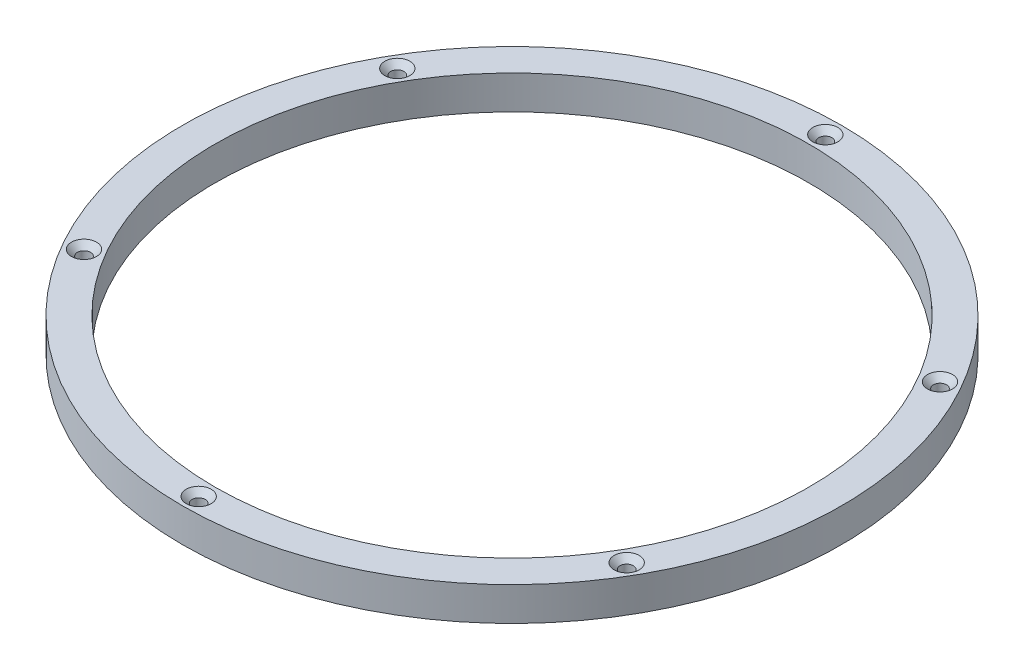
SolidWorks part; units mm, degrees
ref_plane "Front Plane" through (0, 0, 0) normal (0, 0, 1) x (1, 0, 0)
ref_plane "Top Plane" through (0, 0, 0) normal (0, 1, 0) x (1, 0, 0)
ref_plane "Right Plane" through (0, 0, 0) normal (1, 0, 0) x (0, 0, -1)
sketch "Sketch1" plane through (0, 0, 0) normal (0, 1, 0) x (1, 0, 0)
  circle A1 centre (0, 0) radius 137
  circle A2 centre (0, 0) radius 123.5
  dimension "D1" = 13.5
  dimension "D2" = 247
extrude "Boss-Extrude1" add sketch "Sketch1" along normal blind 14
sketch "Sketch2" plane through (0, 14, 0) normal (0, 1, 0) x (1, 0, 0)
  line L0 (0, 137) -> (0, 123.5) construction
  line L1 (0, -123.5) -> (0, -137) construction
  circle A0 centre (0, 0) radius 137 construction
  circle A1 centre (0, 0) radius 123.5 construction
  circle A2 centre (0, 0) radius 130.25
  point P11 (0, -130.25)
  point P18 (0, 130.25)
hole_wizard "CSK for M5 Flat Head Machine Screw1" positions "Sketch3" profile "Sketch4" countersink size "M5" standard "ANSI Metric" end condition through all
sketch "Sketch3" plane through (0, 14, 0) normal (0, 1, 0) x (1, 0, 0)
  line L0 (0, 137) -> (0, 123.5) construction
  point P0 (0, 130.25)
sketch "Sketch4" plane through (0, 14, -130.25) normal (1, 0, 0) x (0, 0, 1)
  line L0 (0, 0) -> (0, 14)
  line L1 (0, 14) -> (2.75, 14)
  line L2 (2.75, 14) -> (2.75, 2.45)
  line L3 (2.75, 2.45) -> (5.2, 0)
  line L5 (5.2, 0) -> (0, 0)
  line L6 (-2.75, 2.45) -> (-5.2, 0) construction
  line L11 (0, -6.35) -> (0, 107.95) construction
  dimension "Thru Hole Dia." = 5.5
  dimension "Thru Hole Depth" = 14
  dimension "Near C'Sink Dia." = 10.4
  dimension "Near C'Sink Angle" = 90
pattern_circular "CirPattern1" count 6 over 360 about axis through (0, 0, 0) along (0, 1, 0) of "CSK for M5 Flat Head Machine Screw1"
